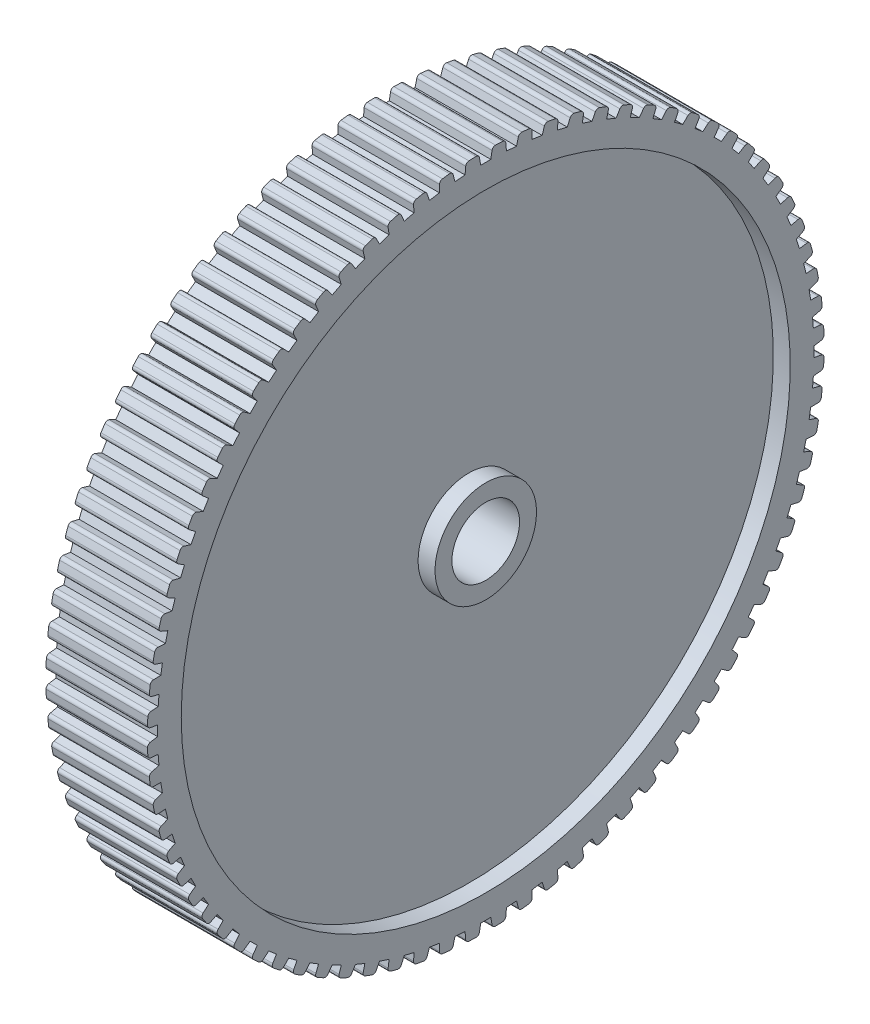
SolidWorks part; units mm, degrees
ref_plane "Front Plane" through (0, 0, 0) normal (0, 0, 1) x (1, 0, 0)
ref_plane "Top Plane" through (0, 0, 0) normal (0, 1, 0) x (1, 0, 0)
ref_plane "Right Plane" through (0, 0, 0) normal (1, 0, 0) x (0, 0, -1)
sketch "Sketch1" plane through (0, 0, 0) normal (0, 0, 1) x (1, 0, 0)
  line L0 (-291.1203, 205.7124) -> (563.3586, 205.7124) construction
  line L13 (66.5009, 215.7124) -> (96.5009, 215.7124)
  line L14 (96.5009, 215.7124) -> (96.5009, 220.7124)
  line L15 (96.5009, 220.7124) -> (91.5009, 220.7124)
  line L16 (91.5009, 220.7124) -> (91.5009, 295.7124)
  line L17 (91.5009, 295.7124) -> (96.5009, 295.7124)
  line L18 (96.5009, 295.7124) -> (96.5009, 305.7124)
  line L19 (96.5009, 305.7124) -> (66.5009, 305.7124)
  line L20 (66.5009, 305.7124) -> (66.5009, 295.7124)
  line L21 (66.5009, 295.7124) -> (71.5009, 295.7124)
  line L22 (71.5009, 295.7124) -> (71.5009, 220.7124)
  line L23 (71.5009, 220.7124) -> (66.5009, 220.7124)
  line L24 (66.5009, 220.7124) -> (66.5009, 215.7124)
  dimension "D1" = 10
  dimension "D2" = 100
  dimension "D3" = 5
  dimension "D4" = 10
  dimension "D5" = 20
  dimension "D6" = 30
revolve "Revolve1" add sketch "Sketch1" angle 360 about L0
sketch "Sketch4" plane through (96.5009, 0, 0) normal (1, 0, 0) x (0, 0, -1)
  line L0 (-1.5, 302.7124) -> (1.5, 302.7124)
  line L1 (1.5, 302.7124) -> (2.5, 308.7124)
  line L2 (2.5, 308.7124) -> (-2.5, 308.7124)
  line L3 (-2.5, 308.7124) -> (-1.5, 302.7124)
  line L4 (0, 205.7124) -> (0, 68.4662)
  circle A0 centre (0, 205.7124) radius 100 construction
  point P9 (0, 308.7124)
  point P10 (0, 302.7124)
  point P11 (0, 305.7124)
  dimension "D1" = 6
  dimension "D2" = 3
  dimension "D3" = 5
  dimension "D4" = 3
extrude "Cut-Extrude1" cut sketch "Sketch4" against normal blind 36 contours L2 L3 L0 L1
fillet "Fillet1" radius 1 2 edges at (81.5009, 305.6925, 1.9967) (81.5009, 305.6925, -1.9967)
pattern_circular "CirPattern1" count 80 over 360 about axis through (0, 205.7124, 0) along (1, 0, 0) of "Cut-Extrude1", "Fillet1"
